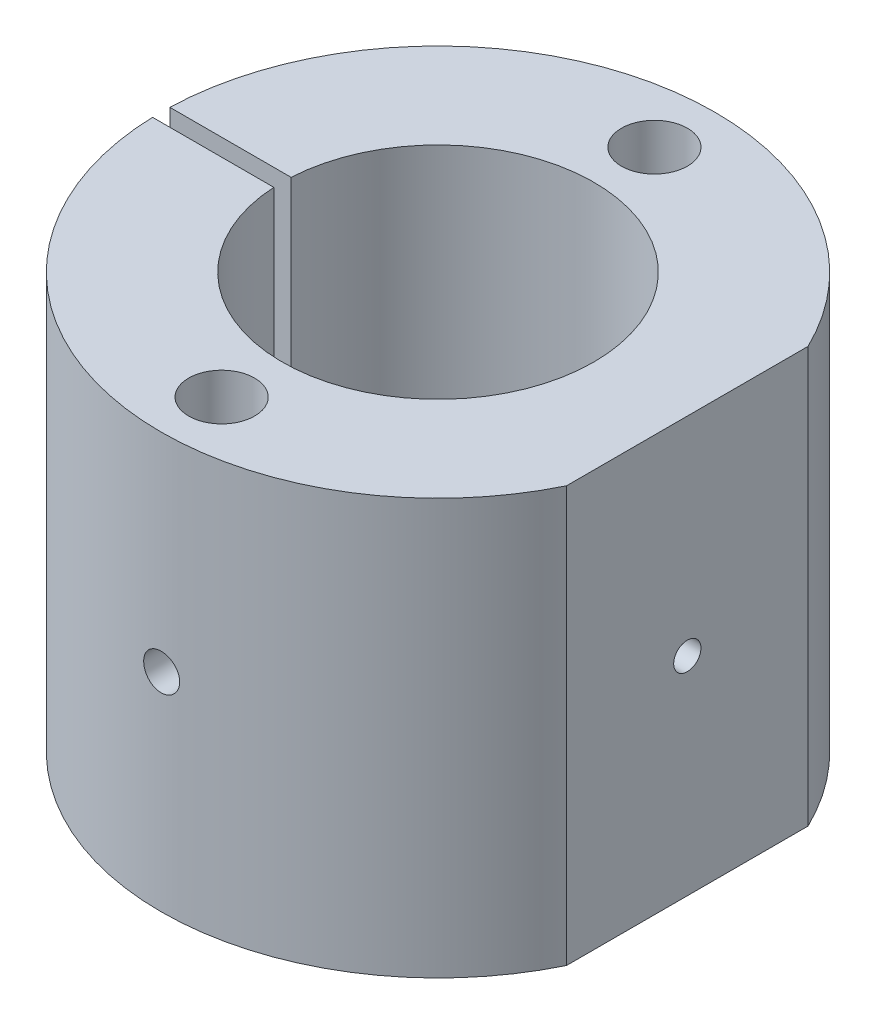
SolidWorks part; units mm, degrees
ref_plane "Front Plane" through (0, 0, 0) normal (0, 0, 1) x (1, 0, 0)
ref_plane "Top Plane" through (0, 0, 0) normal (0, 1, 0) x (1, 0, 0)
ref_plane "Right Plane" through (0, 0, 0) normal (1, 0, 0) x (0, 0, -1)
sketch "Sketch2" plane through (0, 0, 0) normal (0, 1, 0) x (1, 0, 0)
  circle A0 centre (0, 0) radius 14.2875
  circle A1 centre (0, 0) radius 25.4
  dimension "D1" = 50.8
  dimension "D2" = 28.575
extrude "Boss-Extrude1" add sketch "Sketch2" along normal blind 38.1
sketch "Sketch3" plane through (0, 38.1, 0) normal (0, 1, 0) x (1, 0, 0)
  line L0 (0, 0) -> (-25.4, 0) construction
  line L1 (0, 0.7937) -> (-25.4, 0.7937)
  line L2 (0, -0.7937) -> (-25.4, -0.7938)
  line L3 (-25.4, 0.7937) -> (-25.4, -0.7938)
  line L4 (0, 0.7937) -> (0, -0.7937)
  circle A0 centre (0, 0) radius 25.4 construction
  dimension "D1" = 0.7937
  dimension "D2" = 0.7937
extrude "Cut-Extrude1" cut sketch "Sketch3" against normal up to next
sketch "Sketch4" plane through (0, 38.1, 0) normal (0, 1, 0) x (1, 0, 0)
  line L0 (0, -14.2875) -> (0, -25.4) construction
  arc A0 (-14.2654, -0.7938) -> (-14.2654, 0.7937) centre (0, 0) ccw construction
  arc A1 (-25.3876, -0.7938) -> (-25.3876, 0.7937) centre (0, 0) ccw construction
  circle A2 centre (0, -19.8438) radius 3.0226
  dimension "D1" = 6.0452
extrude "Cut-Extrude2" cut sketch "Sketch4" against normal up to next
ref_plane "Plane1" through (0, 0, 25.4) normal (0, 0, 1) x (1, 0, 0)
sketch "Sketch9" plane through (0, 0, 0.7937) normal (0, 0, -1) x (-1, 0, 0)
  line L0 (19.8265, 0) -> (19.8265, 38.1) construction
  line L1 (14.2654, 0) -> (25.3876, 0) construction
  line L2 (25.3876, 38.1) -> (14.2654, 38.1) construction
  circle A0 centre (19.8265, 29.1092) radius 1.0697 construction
  circle A1 centre (19.8265, 8.904) radius 1.0697 construction
hole_wizard "Tap Drill for M4x0.7 Tap1" positions "3DSketch4" profile "Sketch10" hole size "M4x0.7" standard "ANSI Metric"
sketch3d "3DSketch4"
  point P0 (-19.8265, 29.1092, 0.7938)
  point P3 (-19.8265, 8.904, 0.7938)
sketch "Sketch10" plane through (-19.8265, 29.1092, 0.7938) normal (1, 0, 0) x (0, 1, 0)
  line L0 (0, 0) -> (0, 15.0829)
  line L1 (0, 15.0829) -> (1.65, 15.0829)
  line L2 (1.65, 15.0829) -> (1.65, 0)
  line L5 (1.65, 0) -> (0, 0)
  line L11 (0, -6.35) -> (0, 107.95) construction
  dimension "Thru Hole Dia." = 3.3
  dimension "Thru Hole Depth" = 15.0829
sketch "Sketch11" plane through (0, 0, 25.4) normal (0, 0, 1) x (1, 0, 0)
  line L0 (0.0062, 0) -> (0.0062, 38.1) construction
  line L1 (-25.3876, 0) -> (25.4, 0) construction
  line L2 (25.4, 38.1) -> (-25.3876, 38.1) construction
  circle A0 centre (0.0062, 19.05) radius 1.65
  dimension "D1" = 3.3
extrude "Cut-Extrude5" cut sketch "Sketch11" against normal up to next
mirror "Mirror1" about plane through (0, 0, 0) normal (0, 0, 1) of "Cut-Extrude2", "Cut-Extrude5"
sketch "Sketch12" plane through (0, 38.1, 0) normal (0, 1, 0) x (1, 0, 0)
  line L0 (22.86, 11.0716) -> (22.86, -11.0716)
  arc A0 (-25.3876, -0.7938) -> (-25.3876, 0.7937) centre (0, 0) ccw construction
  arc A1 (22.86, -11.0716) -> (22.86, 11.0716) centre (0, 0) ccw
  arc A2 (-14.2654, -0.7938) -> (-14.2654, 0.7937) centre (0, 0) ccw construction
  dimension "D1" = 22.86
extrude "Cut-Extrude6" cut sketch "Sketch12" against normal up to next
sketch "Sketch13" plane through (22.86, 0, 0) normal (1, 0, 0) x (0, 0, -1)
  line L0 (0, 38.1) -> (0, 0) construction
  line L1 (11.0716, 38.1) -> (-11.0716, 38.1) construction
  line L2 (-11.0716, 0) -> (11.0716, 0) construction
  circle A0 centre (0, 19.05) radius 1.15 construction
  dimension "D1" = 2.3
hole_wizard "Tap Drill for M3x0.5 Tap2" positions "3DSketch5" profile "Sketch14" hole size "M3x0.5" standard "ANSI Metric"
sketch3d "3DSketch5"
  point P0 (22.86, 19.05, 0)
sketch "Sketch14" plane through (22.86, 19.05, 0) normal (0, 1, 0) x (0, 0, -1)
  line L0 (0, 0) -> (0, 5.3231)
  line L1 (0, 5.3231) -> (1.25, 4.572)
  line L2 (1.25, 4.572) -> (1.25, 0)
  line L5 (1.25, 0) -> (0, 0)
  line L10 (0, 5.3231) -> (-1.25, 4.572) construction
  line L11 (0, -6.35) -> (0, 107.95) construction
  dimension "Hole Dia." = 2.5
  dimension "Hole Depth" = 4.572
  dimension "Drill Angle" = 118
sketch "Sketch15" plane through (0, 0, 0.7937) normal (0, 0, -1) x (-1, 0, 0)
  line L0 (19.8265, 0) -> (19.8265, 38.1) construction
  line L1 (19.8265, 0) -> (19.8265, 38.1) construction
  circle A0 centre (19.8265, 19.05) radius 2.665
  dimension "D1" = 5.33
hole_wizard "Tap Drill for M5x0.8 Tap1" positions "3DSketch7" profile "Sketch17" hole size "M5x0.8" standard "ANSI Metric"
sketch3d "3DSketch7"
  point P0 (-19.8265, 19.05, 0.7938)
sketch "Sketch17" plane through (-19.8265, 19.05, 0.7938) normal (1, 0, 0) x (0, 1, 0)
  line L0 (0, 0) -> (0, 15.0829)
  line L1 (0, 15.0829) -> (2.1, 15.0829)
  line L2 (2.1, 15.0829) -> (2.1, 0)
  line L5 (2.1, 0) -> (0, 0)
  line L11 (0, -6.35) -> (0, 107.95) construction
  dimension "Thru Hole Dia." = 4.2
  dimension "Thru Hole Depth" = 15.0829
extrude "Cut-Extrude7" cut sketch "Sketch15" along normal through all
ref_plane "Plane2" through (0, 0, -8.7937) normal (0, 0, 1) x (1, 0, 0)
sketch "Sketch19" plane through (0, 0, -8.7937) normal (0, 0, 1) x (1, 0, 0)
  circle A0 centre (-19.8265, 19.05) radius 5
  dimension "D1" = 10
extrude "Cut-Extrude8" cut sketch "Sketch19" against normal up to next
sketch "Sketch21" plane through (0, 0, 0) normal (0, -1, 0) x (1, 0, 0)
  line L0 (22.86, 0) -> (14.2875, 0) construction
  line L1 (18.5737, -10) -> (18.5738, 0) construction
  arc A0 (-14.2654, -0.7937) -> (-14.2654, 0.7938) centre (0, 0) ccw construction
  circle A1 centre (18.5737, -10) radius 2.665
  circle A2 centre (18.5737, 10) radius 2.665
  dimension "D1" = 5.33
  dimension "D2" = 10
extrude "Cut-Extrude10" cut sketch "Sketch21" against normal blind 10
